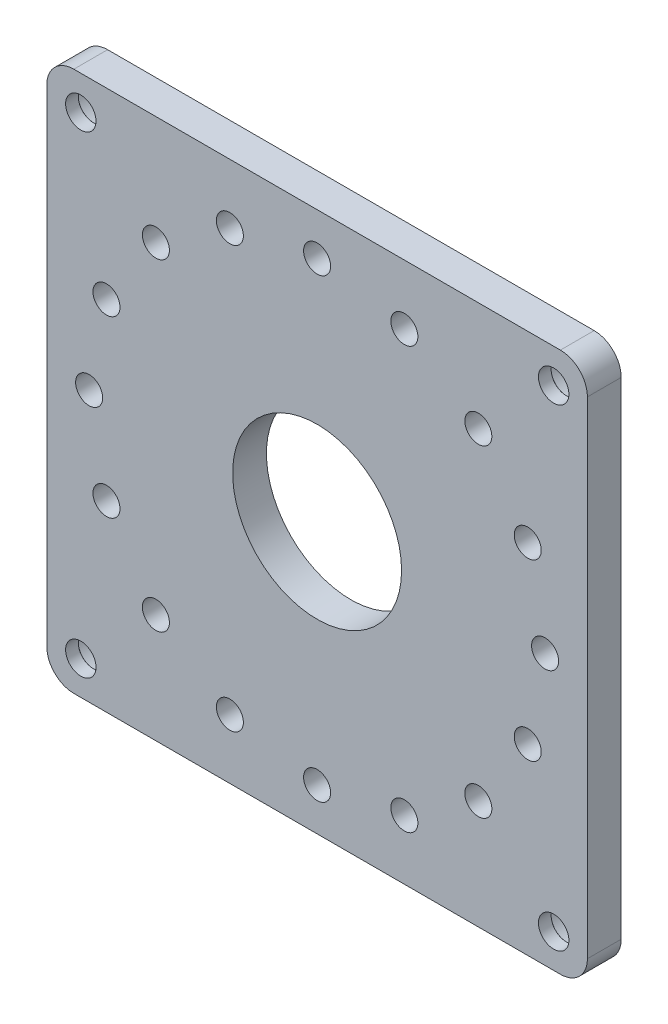
SolidWorks part; units mm, degrees
ref_plane "Plan de face" through (0, 0, 0) normal (0, 0, 1) x (1, 0, 0)
ref_plane "Plan de dessus" through (0, 0, 0) normal (0, 1, 0) x (1, 0, 0)
ref_plane "Plan de droite" through (0, 0, 0) normal (1, 0, 0) x (0, 0, -1)
sketch "Esquisse1" plane through (0, 0, 0) normal (0, 0, 1) x (1, 0, 0)
  line L1 (-36, -40) -> (36, -40)
  line L2 (-40, -36) -> (-40, 36)
  line L3 (-36, 40) -> (36, 40)
  line L4 (40, -36) -> (40, 36)
  line L5 (-40, -40) -> (40, 40) construction
  line L6 (-40, 40) -> (40, -40) construction
  circle A0 centre (0, 0) radius 12.5
  circle A1 centre (0, 0) radius 33.7388 construction
  circle A2 centre (0, 33.7388) radius 2
  circle A3 centre (0, 0) radius 33.7388 construction
  circle A4 centre (12.9113, 31.1706) radius 2
  circle A5 centre (0, 0) radius 33.7388 construction
  circle A6 centre (23.8569, 23.8569) radius 2
  circle A7 centre (0, 0) radius 33.7388 construction
  circle A8 centre (31.1706, 12.9113) radius 2
  circle A9 centre (0, 0) radius 33.7388 construction
  circle A10 centre (33.7388, 0) radius 2
  circle A11 centre (0, 0) radius 33.7388 construction
  circle A12 centre (31.1706, -12.9113) radius 2
  circle A13 centre (0, 0) radius 33.7388 construction
  circle A14 centre (23.8569, -23.8569) radius 2
  circle A15 centre (0, 0) radius 33.7388 construction
  circle A16 centre (12.9113, -31.1706) radius 2
  circle A17 centre (0, 0) radius 33.7388 construction
  circle A18 centre (0, -33.7388) radius 2
  circle A19 centre (0, 0) radius 33.7388 construction
  circle A20 centre (-12.9113, -31.1706) radius 2
  circle A21 centre (0, 0) radius 33.7388 construction
  circle A22 centre (-23.8569, -23.8569) radius 2
  circle A23 centre (0, 0) radius 33.7388 construction
  circle A24 centre (-31.1706, -12.9113) radius 2
  circle A25 centre (0, 0) radius 33.7388 construction
  circle A26 centre (-33.7388, 0) radius 2
  circle A27 centre (0, 0) radius 33.7388 construction
  circle A28 centre (-31.1706, 12.9113) radius 2
  circle A29 centre (0, 0) radius 33.7388 construction
  circle A30 centre (-23.8569, 23.8569) radius 2
  circle A31 centre (0, 0) radius 33.7388 construction
  circle A32 centre (-12.9113, 31.1706) radius 2
  arc A33 (-36, -40) -> (-40, -36) centre (-36, -36) cw
  arc A34 (36, -40) -> (40, -36) centre (36, -36) ccw
  arc A35 (40, 36) -> (36, 40) centre (36, 36) ccw
  arc A36 (-40, 36) -> (-36, 40) centre (-36, 36) cw
  point P0 (0, 0)
  point P59 (0, 0)
  dimension "D3" = 25
  dimension "D4" = 4
  dimension "D6" = 4
  dimension "D1" = 80
  dimension "D2" = 80
  dimension "D5" = 16
extrude "Boss.-Extru.1" add sketch "Esquisse1" along normal blind 5
hole_wizard "Dégagement M41" positions "Esquisse9" profile "Esquisse8" hole size "M4" standard "JIS" end condition through all
sketch "Esquisse9" plane through (0, 0, 5) normal (0, 0, 1) x (1, 0, 0)
  point P0 (-34.9684, 34.9624)
  point P2 (-34.9684, -35.0239)
  point P4 (35.0076, -35.0239)
  point P6 (35.0076, 34.9624)
sketch "Esquisse8" plane through (-34.9684, 34.9624, 5) normal (1, 0, 0) x (0, -1, 0)
  line L0 (0, 0) -> (0, 5)
  line L1 (0, 5) -> (2.25, 5)
  line L2 (2.25, 5) -> (2.25, 0)
  line L5 (2.25, 0) -> (0, 0)
  line L11 (0, -6.35) -> (0, 107.95) construction
  dimension "Diamètre du perçage jusqu'au prochain" = 4.5
  dimension "Profondeur du perçage jusqu'au prochain" = 5
hole_wizard "Chambrage pour vis à tête ronde bombée M41" positions "Esquisse11" profile "Esquisse10" counterbore size "M4" standard "Ansi Metric" end condition through all
sketch "Esquisse11" plane through (0, 0, 0) normal (0, 0, -1) x (-1, 0, 0)
  point P0 (-35.0076, 34.9624)
  point P2 (34.9684, 34.9624)
  point P4 (34.9684, -35.0239)
  point P6 (-35.0076, -35.0239)
sketch "Esquisse10" plane through (35.0076, 34.9624, 0) normal (1, 0, 0) x (0, 1, 0)
  line L0 (0, 0) -> (0, 5)
  line L1 (0, 5) -> (2.25, 5)
  line L2 (2.25, 3.125) -> (2.25, 5)
  line L3 (2.25, 3.125) -> (2.275, 3.1)
  line L4 (2.275, 3.1) -> (4.5, 3.1)
  line L5 (4.5, 3.1) -> (4.5, 0)
  line L7 (0, 0) -> (4.5, 0)
  line L9 (-2.25, 3.125) -> (-2.275, 3.1) construction
  line L11 (0, -6.35) -> (0, 107.95) construction
  dimension "Diamètre du perçage jusqu'au prochain" = 4.5
  dimension "Profondeur du perçage jusqu'au prochain" = 5
  dimension "Diamètre du chambrage" = 9
  dimension "Profondeur du chambrage" = 3.1
  dimension "Diamètre du fraisage milieu" = 4.55
  dimension "Angle du fraisage milieu" = 90
